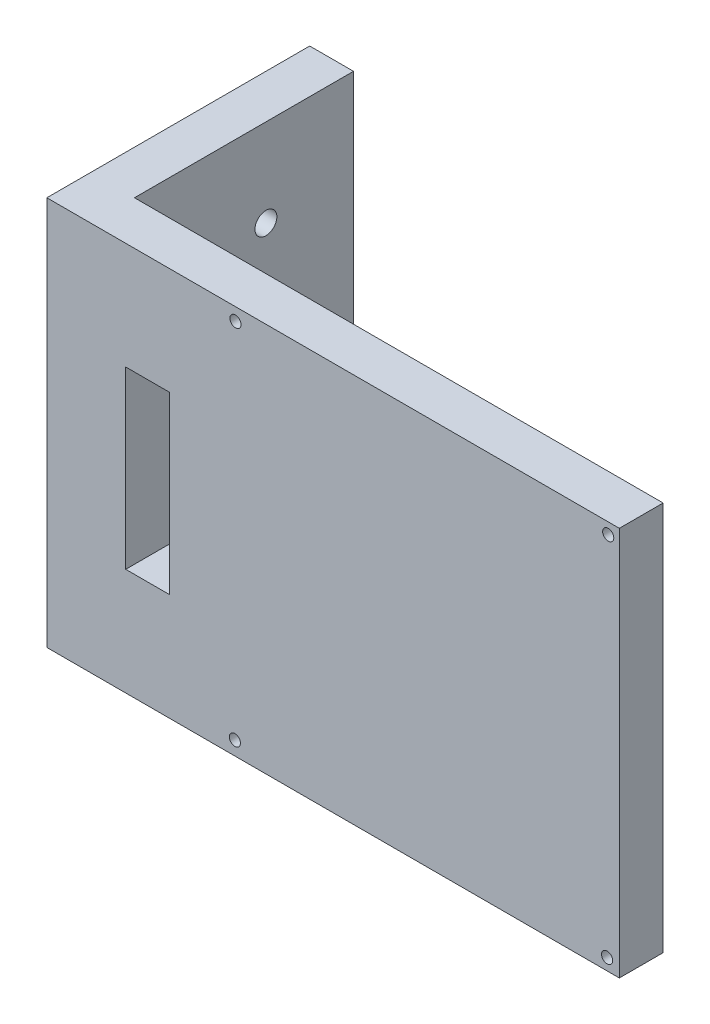
SolidWorks part; units mm, degrees
ref_plane "Front Plane" through (0, 0, 0) normal (0, 0, 1) x (1, 0, 0)
ref_plane "Top Plane" through (0, 0, 0) normal (0, 1, 0) x (1, 0, 0)
ref_plane "Right Plane" through (0, 0, 0) normal (1, 0, 0) x (0, 0, -1)
sketch "Sketch1" plane through (0, 0, 0) normal (0, 0, 1) x (1, 0, 0)
  point P0 (0, 0)
  line B0 (0, 0) -> (90.678, 0)
  line B1 (0, 88.9) -> (0, 0)
  line B2 (90.678, 88.9) -> (0, 88.9)
  line B3 (90.678, 0) -> (90.678, 88.9)
  circle B4 centre (2.921, 3.175) radius 1.27
  circle B5 centre (3.048, 85.979) radius 1.27
  circle B6 centre (87.884, 2.667) radius 1.27
  circle B7 centre (88.138, 86.36) radius 1.27
sketch_block_instance "Block1-1"
sketch_block "Block1"
extrude "Boss-Extrude1" add sketch "Sketch1" along normal blind 10
sketch "Sketch2" plane through (0, 0, 0) normal (-1, 0, 0) x (0, 0, 1)
  line L1 (10, 88.9) -> (0, 88.9)
  line L2 (10, 88.9) -> (10, 0)
  line L3 (10, 0) -> (0, 0)
  line L4 (0, 88.9) -> (0, 0)
  point P5 (-20, 0)
  dimension "D2" = 88.9
extrude "Boss-Extrude2" add sketch "Sketch2" along normal blind 30
sketch "Sketch5" plane through (0, 0, 10) normal (0, 0, 1) x (1, 0, 0)
  line L0 (90.678, 88.9) -> (-30, 88.9) construction
  line L1 (-22, 64.45) -> (-12, 64.45)
  line L2 (-22, 64.45) -> (-22, 24.45)
  line L3 (-22, 24.45) -> (-12, 24.45)
  line L4 (-12, 64.45) -> (-12, 24.45)
  line L5 (-22, 64.45) -> (-12, 24.45) construction
  line L6 (-22, 24.45) -> (-12, 64.45) construction
  line L8 (-30, 0) -> (-30, 88.9) construction
  point P0 (-17, 44.45)
  dimension "D1" = 8
  dimension "D2" = 44.45
  dimension "D3" = 40
  dimension "D4" = 10
extrude "Cut-Extrude1" cut sketch "Sketch5" against normal blind 10
sketch "Sketch7" plane through (-30, 0, 0) normal (-1, 0, 0) x (0, 0, 1)
  line L1 (10, 88.9) -> (-50, 88.9)
  line L2 (10, 88.9) -> (10, 0)
  line L3 (10, 0) -> (-50, 0)
  line L4 (-50, 88.9) -> (-50, 0)
  dimension "D1" = 60
  dimension "D2" = 88.9
extrude "Boss-Extrude3" add sketch "Sketch7" along normal blind 10
sketch "Sketch8" plane through (-40, 0, 0) normal (-1, 0, 0) x (0, 0, 1)
  line L0 (10, 88.9) -> (-50, 88.9) construction
  line L1 (10, 0) -> (10, 88.9) construction
  line L2 (10, 44.45) -> (-55.4376, 44.45) construction
  line L3 (-20, 88.9) -> (-20, -6.8841) construction
  circle A0 centre (-10, 68.9) radius 2.5
  circle A1 centre (-10, 20) radius 2.5
  circle A2 centre (-30, 20) radius 2.5
  circle A3 centre (-30, 68.9) radius 2.5
  dimension "D1" = 5
  dimension "D2" = 20
  dimension "D3" = 20
extrude "Cut-Extrude2" cut sketch "Sketch8" against normal blind 10
